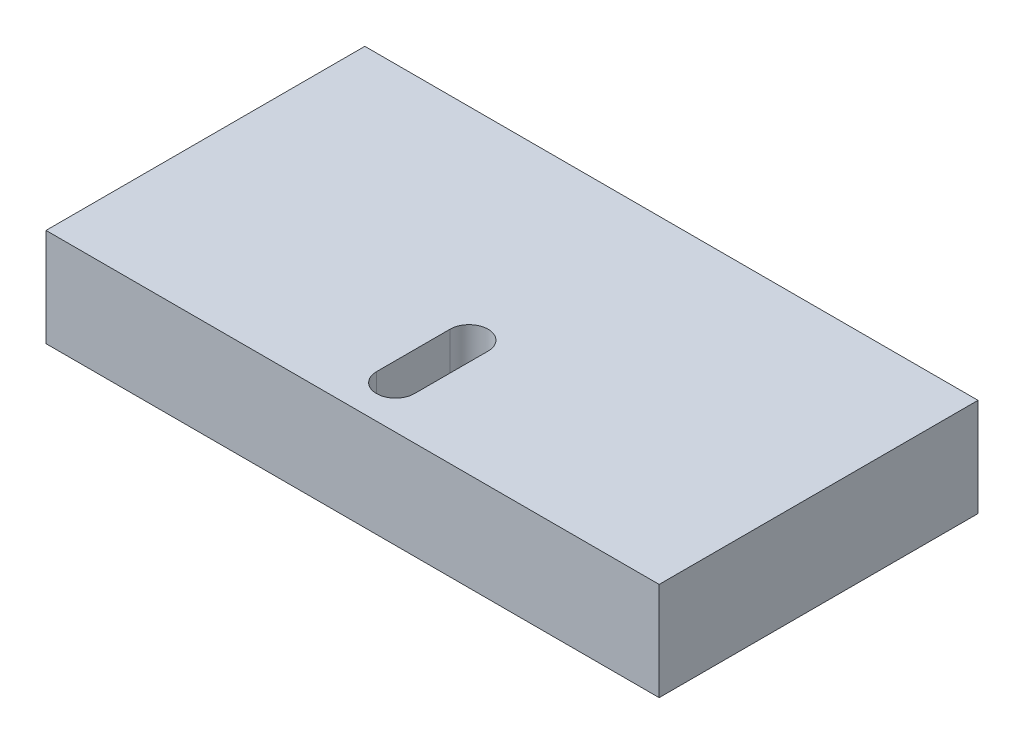
SolidWorks part; units mm, degrees
ref_plane "Alzado" through (0, 0, 0) normal (0, 0, 1) x (1, 0, 0)
ref_plane "Planta" through (0, 0, 0) normal (0, 1, 0) x (1, 0, 0)
ref_plane "Vista lateral" through (0, 0, 0) normal (1, 0, 0) x (0, 0, -1)
sketch "Croquis1" plane through (0, 0, 0) normal (0, 1, 0) x (1, 0, 0)
  line L0 (0, 0) -> (0, -13) construction
  line L1 (-25, -13) -> (25, -13)
  line L2 (-25, -13) -> (-25, 13)
  line L3 (-25, 13) -> (25, 13)
  line L4 (25, -13) -> (25, 13)
  line L5 (-25, -13) -> (25, 13) construction
  line L6 (-25, 13) -> (25, -13) construction
  line L7 (0, -9.5) -> (0, -3.5) construction
  line L8 (-1.55, -9.5) -> (-1.55, -3.5)
  line L9 (1.55, -9.5) -> (1.55, -3.5)
  arc A0 (-1.55, -9.5) -> (1.55, -9.5) centre (0, -9.5) ccw
  arc A1 (1.55, -3.5) -> (-1.55, -3.5) centre (0, -3.5) ccw
  point P0 (0, 0)
  point P10 (0, -6.5)
  dimension "D4" = 1.55
  dimension "D1" = 50
  dimension "D2" = 26
  dimension "D3" = 6
extrude "Saliente-Extruir1" add sketch "Croquis1" along normal blind 8
